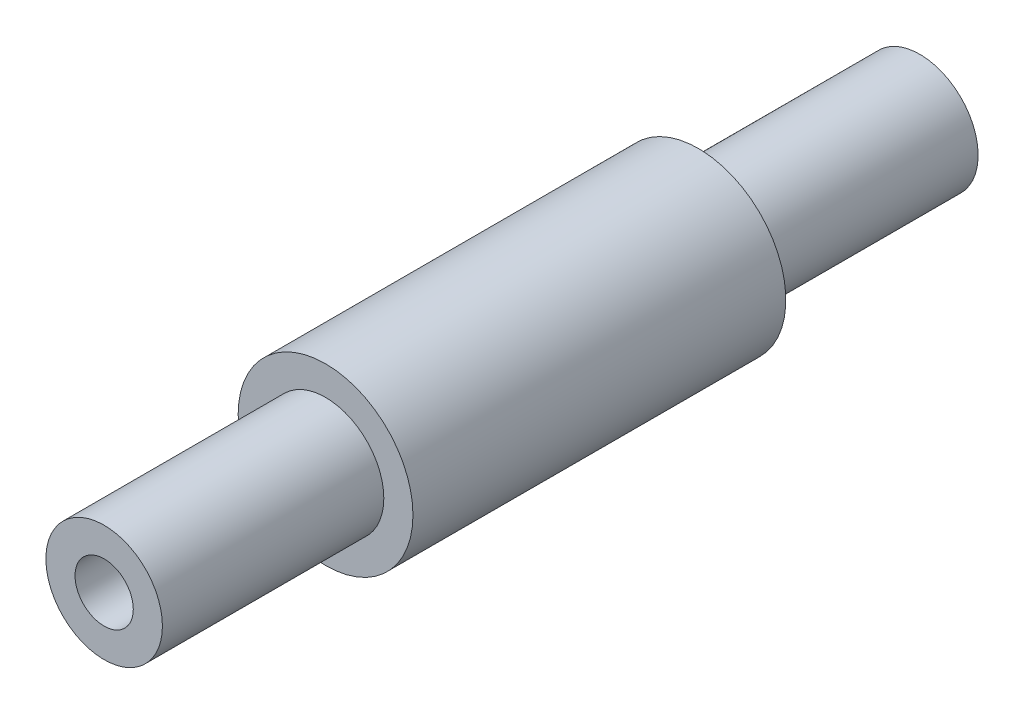
SolidWorks part; units mm, degrees
ref_plane "Ön Düzlem" through (0, 0, 0) normal (0, 0, 1) x (1, 0, 0)
ref_plane "Üst Düzlem" through (0, 0, 0) normal (0, 1, 0) x (1, 0, 0)
ref_plane "Sağ Düzlem" through (0, 0, 0) normal (1, 0, 0) x (0, 0, -1)
sketch "Sketch1" plane through (0, 0, 0) normal (0, 0, 1) x (1, 0, 0)
  circle A0 centre (0, 0) radius 7.5
  dimension "D1" = 15
extrude "Boss-Extrude1" add sketch "Sketch1" along normal blind 70
sketch "Sketch2" plane through (0, 0, 0) normal (0, 0, -1) x (-1, 0, 0)
  circle A0 centre (0, 0) radius 5
  circle A1 centre (0, 0) radius 10.1944
  dimension "D1" = 10
extrude "Cut-Extrude1" cut sketch "Sketch2" against normal blind 19
sketch "Sketch3" plane through (0, 0, 70) normal (0, 0, 1) x (1, 0, 0)
  circle A0 centre (0, 0) radius 5
  circle A1 centre (0, 0) radius 9.9519
  dimension "D1" = 10
extrude "Cut-Extrude2" cut sketch "Sketch3" against normal blind 19
sketch "Sketch4" plane through (0, 0, 70) normal (0, 0, 1) x (1, 0, 0)
  circle A0 centre (0, 0) radius 2.5
  dimension "D1" = 5
extrude "Cut-Extrude3" cut sketch "Sketch4" against normal blind 10
sketch "Sketch5" plane through (0, 0, 0) normal (0, 0, -1) x (-1, 0, 0)
  circle A0 centre (0, 0) radius 2.5
  dimension "D1" = 5
extrude "Cut-Extrude4" cut sketch "Sketch5" against normal blind 10
